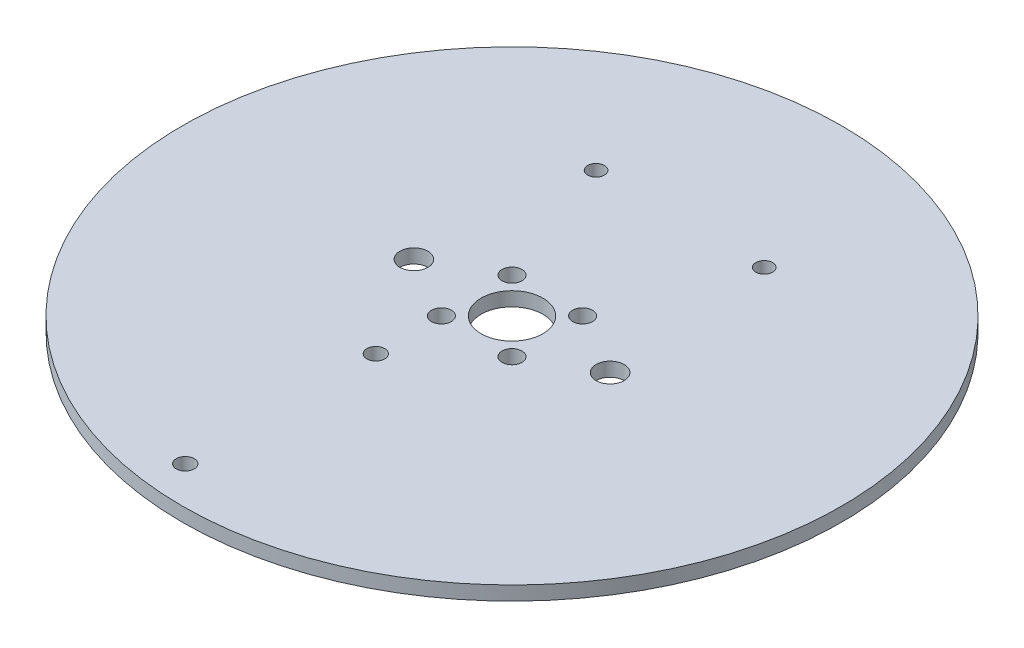
SolidWorks part; units mm, degrees
ref_plane "Front Plane" through (0, 0, 0) normal (0, 0, 1) x (1, 0, 0)
ref_plane "Top Plane" through (0, 0, 0) normal (0, 1, 0) x (1, 0, 0)
ref_plane "Right Plane" through (0, 0, 0) normal (1, 0, 0) x (0, 0, -1)
sketch "Sketch1" plane through (0, 0, 0) normal (0, 1, 0) x (1, 0, 0)
  circle A0 centre (0, 0) radius 74.676
  dimension "D1" = 149.352
extrude "Boss-Extrude1" add sketch "Sketch1" along normal blind 3.175
sketch "Sketch2" plane through (0, 3.175, 0) normal (0, 1, 0) x (1, 0, 0)
  circle A0 centre (0, 0) radius 7
extrude "Cut-Extrude1" cut sketch "Sketch2" against normal up to next
sketch "Sketch4" plane through (0, 3.175, 0) normal (0, 1, 0) x (1, 0, 0)
  circle A0 centre (-22.225, 0) radius 3.175 construction
  circle A1 centre (22.225, 0) radius 3.175 construction
  circle A2 centre (-22.225, 0) radius 3.175
  circle A3 centre (22.225, 0) radius 3.175
extrude "Cut-Extrude3" cut sketch "Sketch4" against normal through all both
hole_wizard "M4 Clearance Hole1" positions "Sketch5" profile "Sketch6" hole size "M4" standard "ANSI Metric" end condition up to next
sketch "Sketch5" plane through (0, 3.175, 0) normal (0, 1, 0) x (1, 0, 0)
  line L0 (-8, 8) -> (8, 8) construction
  line L1 (8, 8) -> (8, -8) construction
  line L2 (0, -1.7463) -> (0, 1.7463) construction
  line L4 (-1.7463, 0) -> (1.7463, 0) construction
  point P0 (-8, 8)
  point P2 (8, 8)
  point P4 (8, -8)
  point P6 (-8, -8)
  point P21 (0, 8)
  point P26 (8, 0)
  dimension "D1" = 16
  dimension "D2" = 16
sketch "Sketch6" plane through (-8, 3.175, -8) normal (1, 0, 0) x (0, 0, 1)
  line L0 (0, 0) -> (0, 3.175)
  line L1 (0, 3.175) -> (2.25, 3.175)
  line L2 (2.25, 3.175) -> (2.25, 0)
  line L5 (2.25, 0) -> (0, 0)
  line L11 (0, -6.35) -> (0, 107.95) construction
  dimension "Thru Hole Dia." = 4.5
  dimension "Thru Hole Depth" = 3.175
sketch "Sketch8" plane through (0, 3.175, 0) normal (0, 1, 0) x (1, 0, 0)
  circle A0 centre (19.05, 38.1) radius 1.8987 construction
  circle A1 centre (-19.05, 38.1) radius 1.8987 construction
  circle A2 centre (19.05, 38.1) radius 1.8987
  circle A3 centre (-19.05, 38.1) radius 1.8987
extrude "Cut-Extrude4" cut sketch "Sketch8" against normal up to next
sketch "Sketch9" plane through (0, 3.175, 0) normal (0, 1, 0) x (1, 0, 0)
  circle A0 centre (-8, -22.86) radius 2.032
  circle A1 centre (-8, -66.04) radius 2.032
  dimension "D1" = 4.064
  dimension "D2" = 43.18
  dimension "D3" = 22.86
extrude "Cut-Extrude5" cut sketch "Sketch9" against normal up to next
